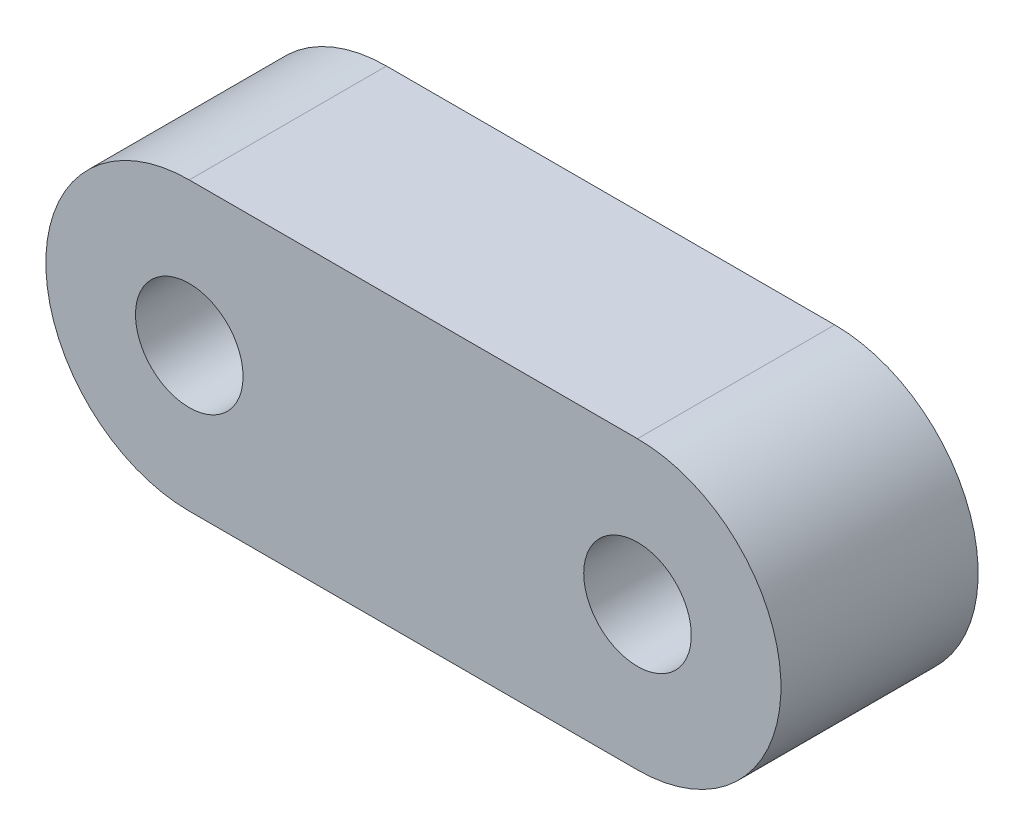
SolidWorks part; units mm, degrees
ref_plane "正面" through (0, 0, 0) normal (0, 0, 1) x (1, 0, 0)
ref_plane "平面" through (0, 0, 0) normal (0, 1, 0) x (1, 0, 0)
ref_plane "右側面" through (0, 0, 0) normal (1, 0, 0) x (0, 0, -1)
sketch "ｽｹｯﾁ1" plane through (0, 0, 0) normal (0, 0, 1) x (1, 0, 0)
  line L0 (0, 0) -> (12.5, 0) construction
  line L1 (0, 4) -> (12.5, 4)
  line L2 (0, -4) -> (12.5, -4)
  line L3 (6.25, 0) -> (6.25, -4) construction
  circle A0 centre (0, 0) radius 1.5
  arc A1 (0, 4) -> (0, -4) centre (0, 0) ccw
  arc A2 (12.5, -4) -> (12.5, 4) centre (12.5, 0) ccw
  circle A3 centre (12.5, 0) radius 1.5
  point P3 (6.25, 0)
  dimension "D1" = 3
  dimension "D3" = 4
  dimension "D2" = 12.5
extrude "ﾎﾞｽ - 押し出し1" add sketch "ｽｹｯﾁ1" along normal blind 5.5 contours L2 A2 L1 A1
sketch "ｽｹｯﾁ2" plane through (0, 0, 0) normal (0, 0, -1) x (-1, 0, 0)
  line L0 (-5, 0) -> (-7.5, 0) construction
  line L1 (-6.25, 0) -> (-10.358, -8.2889) construction
  line L2 (-6.7876, 0.2664) -> (-10.8956, -8.0225)
  line L3 (-4.48, 2.2203) -> (-9.8204, -8.5554)
  line L4 (-5.7124, -0.2664) -> (-9.8204, -8.5554) construction
  circle A0 centre (0, 0) radius 5
  circle A1 centre (-12.5, 0) radius 5
  point P14 (-5, 1.2975)
  point P16 (-4.0193, 2.9741)
  dimension "D1" = 10
  dimension "D2" = 0.6
  dimension "D3" = 0.6
